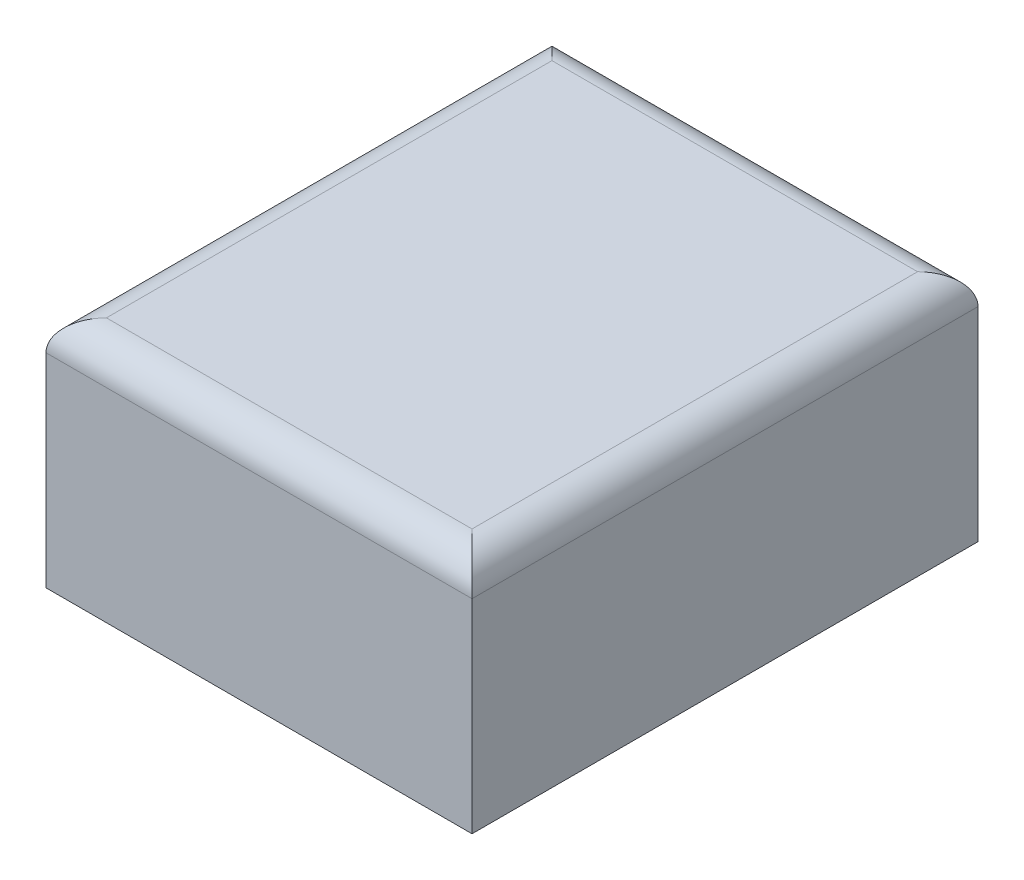
SolidWorks part; units mm, degrees
ref_plane "Front Plane" through (0, 0, 0) normal (0, 0, 1) x (1, 0, 0)
ref_plane "Top Plane" through (0, 0, 0) normal (0, 1, 0) x (1, 0, 0)
ref_plane "Right Plane" through (0, 0, 0) normal (1, 0, 0) x (0, 0, -1)
sketch "Sketch2" plane through (0, 0, 0) normal (0, 1, 0) x (1, 0, 0)
  line L0 (-35.2598, 41.874) -> (35.2598, 41.874)
  line L1 (-35.2598, 41.874) -> (-35.2598, -41.874)
  line L2 (-35.2598, -41.874) -> (35.2598, -41.874)
  line L3 (35.2598, 41.874) -> (35.2598, -41.874)
extrude "Boss-Extrude1" add sketch "Sketch2" along normal blind 38.7
fillet "Fillet1" radius 5 4 edges at (0, 38.7, -41.874) (35.2598, 38.7, 0) (-35.2598, 38.7, 0) (0, 38.7, 41.874)
